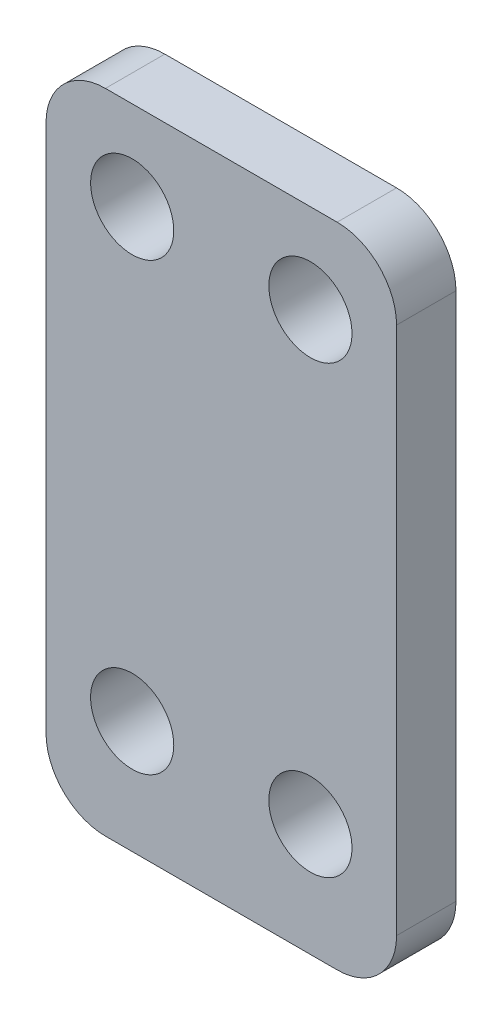
SolidWorks part; units mm, degrees
material "环氧板"
ref_plane "前视基准面" through (0, 0, 0) normal (0, 0, 1) x (1, 0, 0)
ref_plane "上视基准面" through (0, 0, 0) normal (0, 1, 0) x (1, 0, 0)
ref_plane "右视基准面" through (0, 0, 0) normal (1, 0, 0) x (0, 0, -1)
other "Configuration Table"
sketch "草图1" plane through (0, 0, 0) normal (0, 0, 1) x (1, 0, 0)
  line L0 (0, 3.13) -> (-18.4836, 3.13) construction
  line L1 (-5.9, 10.9) -> (5.9, 10.9)
  line L2 (-5.9, 10.9) -> (-5.9, -10.9)
  line L3 (-5.9, -10.9) -> (5.9, -10.9)
  line L4 (5.9, 10.9) -> (5.9, -10.9)
  line L5 (-5.9, 10.9) -> (5.9, -10.9) construction
  line L6 (-5.9, -10.9) -> (5.9, 10.9) construction
  line L7 (0, 0) -> (0, 20.16) construction
  circle A0 centre (-3, -7.1) radius 1.4
  circle A1 centre (-3, 7.9) radius 1.4
  circle A2 centre (3, 7.9) radius 1.4
  circle A3 centre (3, -7.1) radius 1.4
  point P0 (0, 0)
  dimension "D3" = 2.8
  dimension "D4" = 6
  dimension "D5" = 15
  dimension "D6" = 3.8
  dimension "D1" = 11.8
  dimension "D2" = 21.8
extrude "凸台-拉伸1" add sketch "草图1" along normal blind 2
fillet "圆角1" radius 2 4 edges at (5.9, -10.9, 1) (-5.9, -10.9, 1) (5.9, 10.9, 1) (-5.9, 10.9, 1)
chamfer "倒角1" [suppressed] distance 1.2 angle 45
